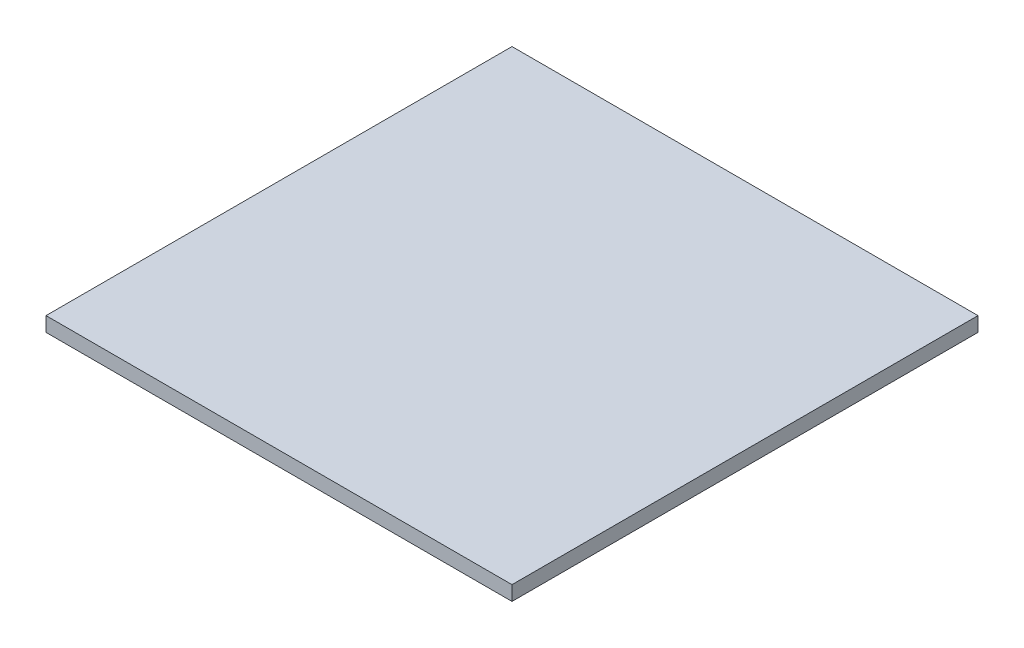
SolidWorks part; units mm, degrees
ref_plane "Front Plane" through (0, 0, 0) normal (0, 0, 1) x (1, 0, 0)
ref_plane "Top Plane" through (0, 0, 0) normal (0, 1, 0) x (1, 0, 0)
ref_plane "Right Plane" through (0, 0, 0) normal (1, 0, 0) x (0, 0, -1)
sketch "Sketch1" plane through (0, 0, 0) normal (0, 0, 1) x (1, 0, 0)
  line L7 (-101.6, -3.175) -> (101.6, -3.175)
  line L8 (-101.6, -3.175) -> (-101.6, 3.175)
  line L9 (-101.6, 3.175) -> (101.6, 3.175)
  line L10 (101.6, -3.175) -> (101.6, 3.175)
  line L11 (-101.6, -3.175) -> (101.6, 3.175) construction
  line L12 (-101.6, 3.175) -> (101.6, -3.175) construction
  point P4 (0, 0)
  point P14 (0, 0)
  dimension "Thickness" = 6.35
  dimension "Width" = 203.2
sketch "Sketch2" plane through (0, 0, 0) normal (0, 1, 0) x (0, 0, -1)
  line L0 (101.6, 101.6) -> (-101.6, 101.6) construction
  point P4 (0, 101.6)
  dimension "Length" = 203.2
sketch "Sketch3" plane through (0, 0, 0) normal (0, 0, 1) x (1, 0, 0)
  line L6 (-101.6, 3.175) -> (101.6, 3.175)
  line L7 (101.6, 3.175) -> (101.6, -3.175)
  line L8 (101.6, -3.175) -> (-101.6, -3.175)
  line L9 (-101.6, -3.175) -> (-101.6, 3.175)
extrude "Boss-Extrude1" add sketch "Sketch3" along normal mid plane 203.2
equation "\"D1@Boss-Extrude1\" = \"Length@Sketch2\""
